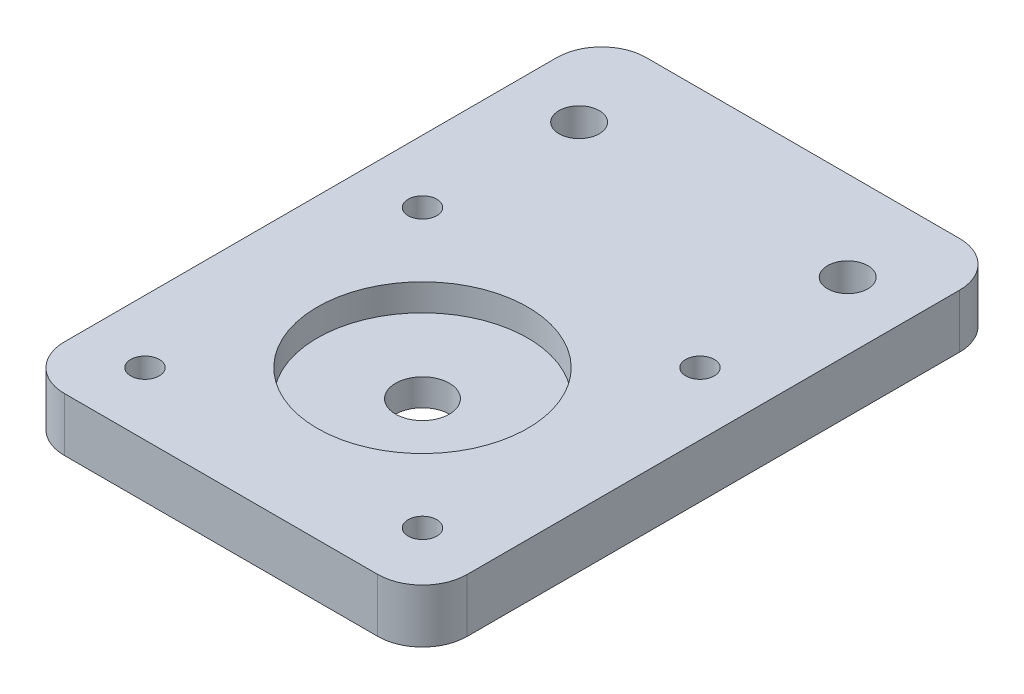
SolidWorks part; units mm, degrees
ref_plane "Front Plane" through (0, 0, 0) normal (0, 0, 1) x (1, 0, 0)
ref_plane "Top Plane" through (0, 0, 0) normal (0, 1, 0) x (1, 0, 0)
ref_plane "Right Plane" through (0, 0, 0) normal (1, 0, 0) x (0, 0, -1)
sketch "Sketch1" plane through (0, 0, 0) normal (0, 1, 0) x (1, 0, 0)
  line L0 (0, 21.921) -> (0, -21.921) construction
  line L1 (-21.921, 0) -> (21.921, 0) construction
  line L2 (0, 0) -> (-15.5005, 15.5005) construction
  line L4 (-22.5, -22.5) -> (22.5, -22.5)
  line L5 (-22.5, -22.5) -> (-22.5, 22.5)
  line L6 (-22.5, 22.5) -> (22.5, 22.5)
  line L7 (22.5, -22.5) -> (-22.5, 22.5) construction
  line L8 (22.5, 22.5) -> (-22.5, -22.5) construction
  line L9 (22.5, -22.5) -> (22.5, 22.5)
  line L10 (-22.5, -22.5) -> (22.5, 22.5) construction
  line L11 (-22.5, 22.5) -> (22.5, -22.5) construction
  circle A0 centre (0, 0) radius 3
  circle A1 centre (0, 0) radius 21.921 construction
  circle A2 centre (-15.5005, 15.5005) radius 1.6
  circle A6 centre (15.5005, 15.5005) radius 1.6
  circle A7 centre (15.5005, -15.5005) radius 1.6
  circle A8 centre (-15.5005, -15.5005) radius 1.6
  point P26 (0, 0)
  dimension "D1" = 6
  dimension "D2" = 43.842
  dimension "D4" = 3.2
  dimension "D3" = 45
  dimension "D5" = 45
  dimension "D6" = 45
  dimension "D7" = 4
extrude "Boss-Extrude1" add sketch "Sketch1" along normal blind 6
sketch "Sketch2" plane through (0, 6, 0) normal (0, 1, 0) x (1, 0, 0)
  circle A0 centre (0, 0) radius 11.75
  dimension "D1" = 23.5
extrude "Cut-Extrude1" cut sketch "Sketch2" against normal blind 3
sketch "Sketch5" plane through (0, 0, 0) normal (0, 1, 0) x (1, 0, 0)
  line L0 (-22.5, 22.5) -> (22.5, 22.5)
  line L1 (22.5, 22.5) -> (22.5, 42.5)
  line L2 (22.5, 42.5) -> (-22.5, 42.5)
  line L3 (-22.5, 42.5) -> (-22.5, 22.5)
  line L4 (0, 48.3016) -> (0, -24.4451) construction
  circle A0 centre (-15, 32.5) radius 2.25
  circle A1 centre (15, 32.5) radius 2.25
  dimension "D1" = 4.5
  dimension "D2" = 20
  dimension "D3" = 10
  dimension "D4" = 45
  dimension "D5" = 15
extrude "Boss-Extrude2" add sketch "Sketch5" along normal up to surface (6 mm away) up to face at (0, 6, 11.75)
fillet "Fillet1" radius 5 4 edges at (22.5, 3, -42.5) (-22.5, 3, -42.5) (22.5, 3, 22.5) (-22.5, 3, 22.5)
equation "\"23。5\"=14.1959"
